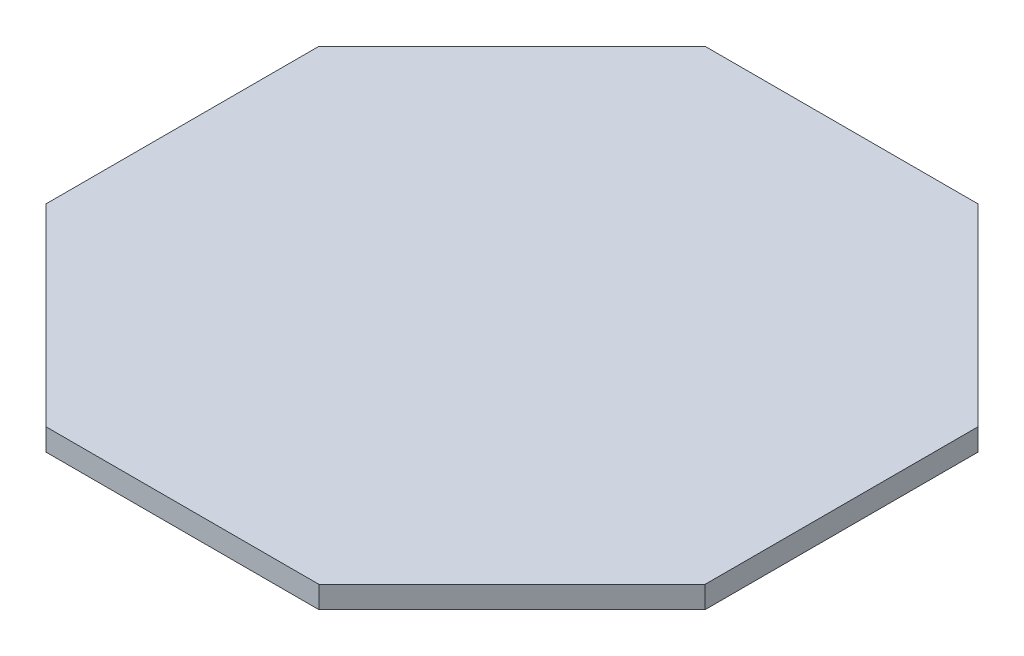
SolidWorks part; units mm, degrees
ref_plane "Front Plane" through (0, 0, 0) normal (0, 0, 1) x (1, 0, 0)
ref_plane "Top Plane" through (0, 0, 0) normal (0, 1, 0) x (1, 0, 0)
ref_plane "Right Plane" through (0, 0, 0) normal (1, 0, 0) x (0, 0, -1)
sketch "Sketch1" plane through (0, 0, 0) normal (0, 1, 0) x (1, 0, 0)
  line L1 (150, -62.132) -> (150, 62.132)
  line L2 (150, 62.132) -> (62.132, 150)
  line L3 (62.132, 150) -> (-62.132, 150)
  line L4 (-62.132, 150) -> (-150, 62.132)
  line L5 (-150, 62.132) -> (-150, -62.132)
  line L6 (-150, -62.132) -> (-62.132, -150)
  line L7 (-62.132, -150) -> (62.132, -150)
  line L8 (62.132, -150) -> (150, -62.132)
  circle A0 centre (0, 0) radius 150 construction
  point P13 (0, 150)
  dimension "D1" = 150
extrude "Boss-Extrude1" add sketch "Sketch1" along normal blind 10
